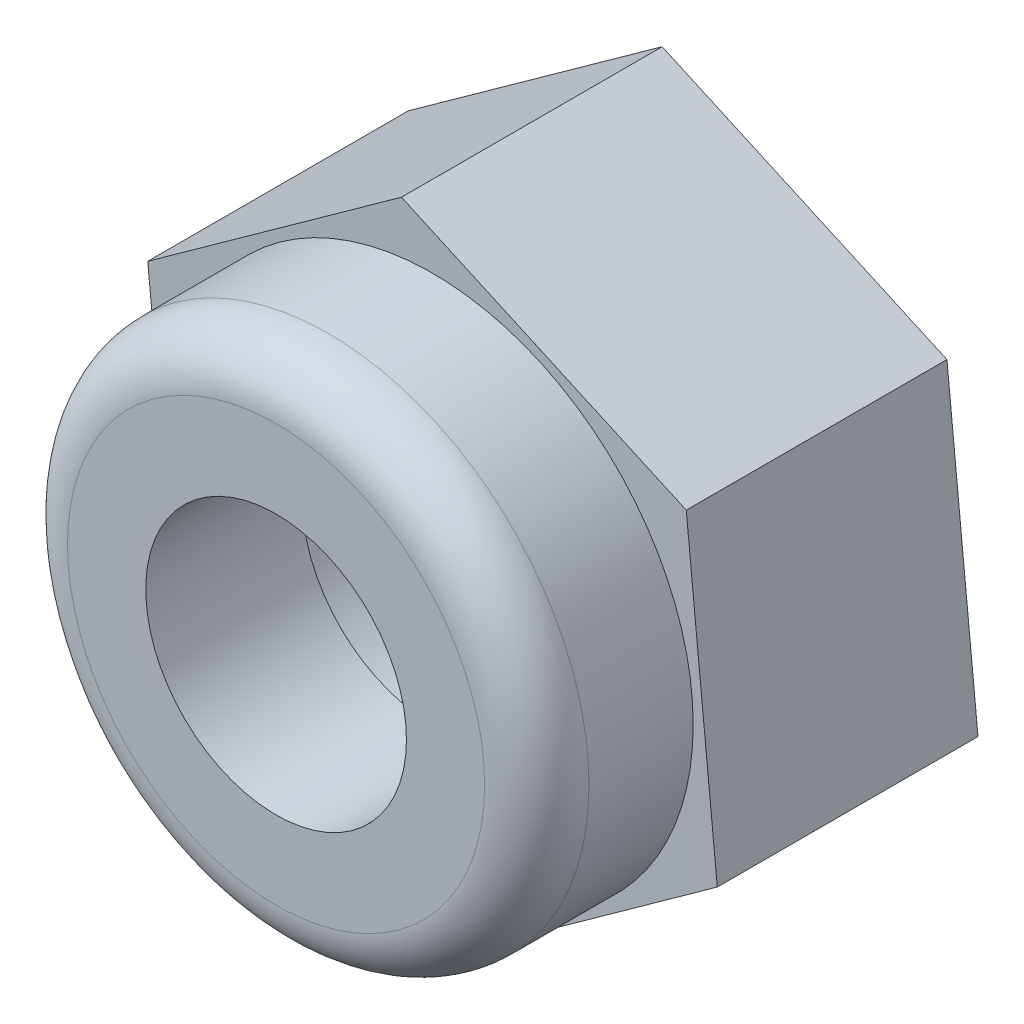
SolidWorks part; units mm, degrees
ref_plane "前视基准面" through (0, 0, 0) normal (0, 0, 1) x (1, 0, 0)
ref_plane "上视基准面" through (0, 0, 0) normal (0, 1, 0) x (1, 0, 0)
ref_plane "右视基准面" through (0, 0, 0) normal (1, 0, 0) x (0, 0, -1)
sketch "草图1" plane through (0, 0, 0) normal (0, 0, 1) x (1, 0, 0)
  circle A0 centre (0, 0) radius 2.5
  circle A1 centre (0, 0) radius 1.25
extrude "凸台-拉伸1" add sketch "草图1" along normal blind 1.5
fillet "圆角1" radius 0.5 1 edges at (2.5, 0, 1.5)
sketch "草图2" plane through (0, 0, 0) normal (0, 0, -1) x (-1, 0, 0)
  line L1 (2.4333, -1.7487) -> (2.731, 1.233)
  line L2 (2.731, 1.233) -> (0.2977, 2.9816)
  line L3 (0.2977, 2.9816) -> (-2.4333, 1.7487)
  line L4 (-2.4333, 1.7487) -> (-2.731, -1.233)
  line L5 (-2.731, -1.233) -> (-0.2977, -2.9816)
  line L6 (-0.2977, -2.9816) -> (2.4333, -1.7487)
  circle A0 centre (0, 0) radius 2.595 construction
  circle A1 centre (0, 0) radius 1.5
extrude "凸台-拉伸2" add sketch "草图2" along normal blind 2.5
